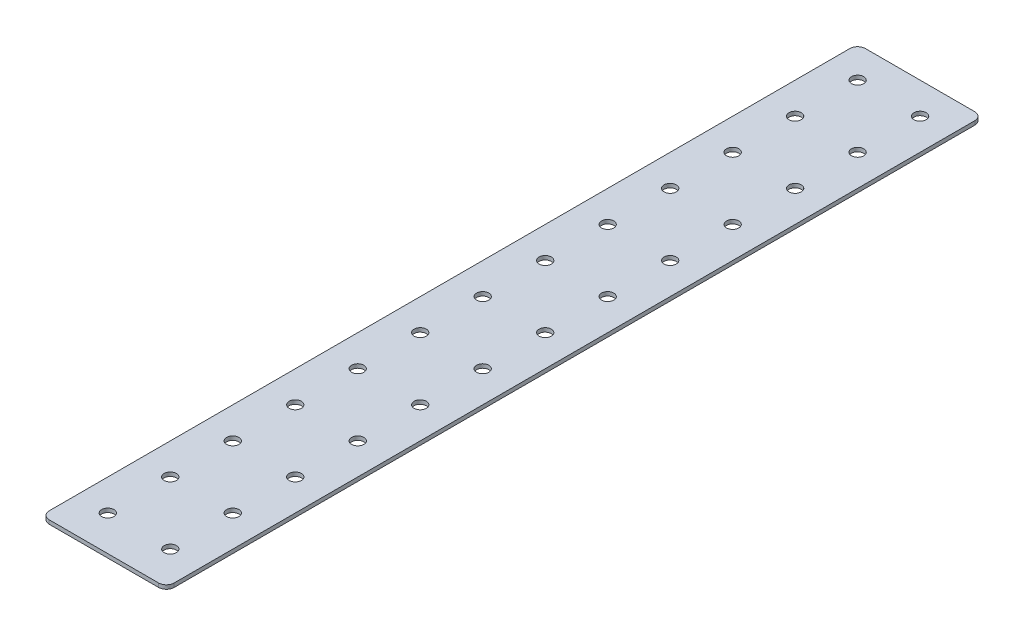
SolidWorks part; units mm, degrees
material "6061-T6 (SS)"
ref_plane "Front Plane" through (0, 0, 0) normal (0, 0, 1) x (1, 0, 0)
ref_plane "Top Plane" through (0, 0, 0) normal (0, 1, 0) x (1, 0, 0)
ref_plane "Right Plane" through (0, 0, 0) normal (1, 0, 0) x (0, 0, -1)
sketch "Sketch1" plane through (0, 0, 0) normal (0, 1, 0) x (1, 0, 0)
  line L1 (0, 0) -> (50.8, 0)
  line L2 (0, 0) -> (0, 331.7875)
  line L3 (0, 331.7875) -> (50.8, 331.7875)
  line L4 (50.8, 0) -> (50.8, 331.7875)
  circle A0 centre (12.7, 14.2875) radius 2.4892
  circle A1 centre (12.7, 39.6875) radius 2.4892
  circle A2 centre (12.7, 65.0875) radius 2.4892
  circle A3 centre (12.7, 90.4875) radius 2.4892
  circle A4 centre (12.7, 115.8875) radius 2.4892
  circle A5 centre (12.7, 141.2875) radius 2.4892
  circle A6 centre (38.1, 39.6875) radius 2.4892
  circle A7 centre (38.1, 65.0875) radius 2.4892
  circle A8 centre (38.1, 90.4875) radius 2.4892
  circle A9 centre (38.1, 115.8875) radius 2.4892
  circle A10 centre (38.1, 141.2875) radius 2.4892
  circle A11 centre (38.1, 14.2875) radius 2.4892
  circle A12 centre (12.7, 166.6875) radius 2.4892
  circle A14 centre (38.1, 166.6875) radius 2.4892
  circle A16 centre (12.7, 192.0875) radius 2.4892 [skipped]
  circle A17 centre (38.1, 192.0875) radius 2.4892 [skipped]
  circle A18 centre (12.7, 319.0875) radius 2.4892
  circle A19 centre (38.1, 319.0875) radius 2.4892
  circle A20 centre (12.7, 293.6875) radius 2.4892
  circle A21 centre (38.1, 293.6875) radius 2.4892
  circle A22 centre (12.7, 268.2875) radius 2.4892
  circle A23 centre (38.1, 268.2875) radius 2.4892
  circle A24 centre (12.7, 242.8875) radius 2.4892
  circle A25 centre (38.1, 242.8875) radius 2.4892
  circle A26 centre (12.7, 217.4875) radius 2.4892
  circle A27 centre (38.1, 217.4875) radius 2.4892
  circle A28 centre (12.7, 192.0875) radius 2.4892
  circle A29 centre (38.1, 192.0875) radius 2.4892
  point P44 (0, 0)
  dimension "D3" = 4.9784
  dimension "D4" = 12.7
  dimension "D5" = 14.2875
  dimension "D10" = 4.9784
  dimension "D15" = 25.4
  dimension "D1" = 50.8
  dimension "D2" = 331.7875
  dimension "D8" = 25.4
  dimension "D9" = 25.4
  dimension "D11" = 25.4
  dimension "D12" = 12.7
  dimension "D13" = 12.7
  dimension "D6" = 8
  dimension "D7" = 2
  dimension "D14" = 6
extrude "Boss-Extrude1" add sketch "Sketch1" along normal blind 1.5875
fillet "Fillet1" radius 3.175 4 edges at (0, 0.7937, -331.7875) (50.8, 0.7937, -331.7875) (0, 0.7937, 0) (50.8, 0.7937, 0)
